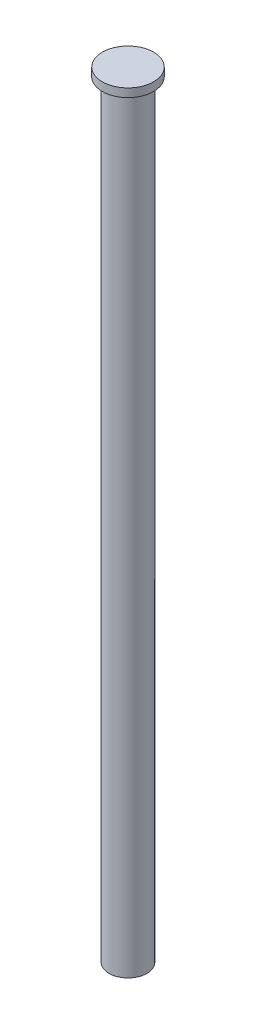
SolidWorks part; units mm, degrees
ref_plane "Front Plane" through (0, 0, 0) normal (0, 0, 1) x (1, 0, 0)
ref_plane "Top Plane" through (0, 0, 0) normal (0, 1, 0) x (1, 0, 0)
ref_plane "Right Plane" through (0, 0, 0) normal (1, 0, 0) x (0, 0, -1)
sketch "Sketch1" plane through (0, 0, 0) normal (0, 1, 0) x (1, 0, 0)
  circle A0 centre (0, 0) radius 22.5
extrude "Boss-Extrude1" add sketch "Sketch1" along normal blind 910
sketch "Sketch2" plane through (0, 910, 0) normal (0, 1, 0) x (1, 0, 0)
  circle A0 centre (0, 0) radius 30.4498
extrude "Boss-Extrude2" add sketch "Sketch2" along normal blind 10
